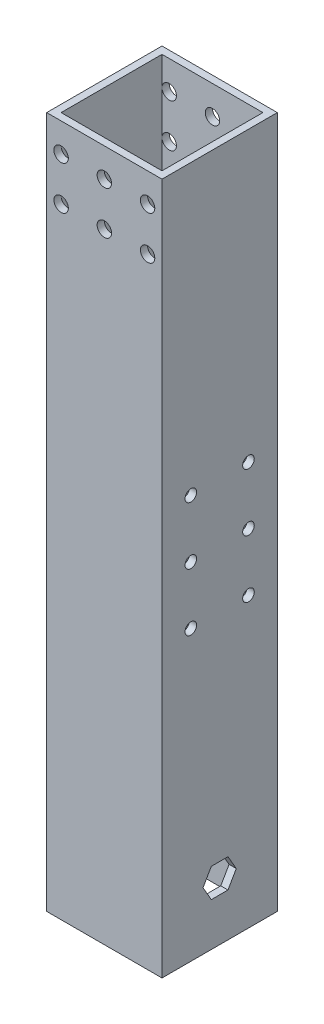
SolidWorks part; units mm, degrees
ref_plane "Front Plane" through (0, 0, 0) normal (0, 0, 1) x (1, 0, 0)
ref_plane "Top Plane" through (0, 0, 0) normal (0, 1, 0) x (1, 0, 0)
ref_plane "Right Plane" through (0, 0, 0) normal (1, 0, 0) x (0, 0, -1)
sketch "Sketch1" plane through (0, 0, 0) normal (0, 1, 0) x (1, 0, 0)
  line L1 (-25.4, -25.4) -> (25.4, -25.4)
  line L2 (-25.4, -25.4) -> (-25.4, 25.4)
  line L3 (-25.4, 25.4) -> (25.4, 25.4)
  line L4 (25.4, -25.4) -> (25.4, 25.4)
  line L5 (-25.4, -25.4) -> (25.4, 25.4) construction
  line L6 (-25.4, 25.4) -> (25.4, -25.4) construction
  line L7 (-22.225, -22.225) -> (22.225, -22.225)
  line L8 (-22.225, -22.225) -> (-22.225, 22.225)
  line L9 (-22.225, 22.225) -> (22.225, 22.225)
  line L10 (22.225, -22.225) -> (22.225, 22.225)
  line L11 (-22.225, -22.225) -> (22.225, 22.225) construction
  line L12 (-22.225, 22.225) -> (22.225, -22.225) construction
  point P0 (0, 0)
  point P6 (0, 0)
  dimension "D1" = 50.8
  dimension "D2" = 50.8
  dimension "D3" = 3.175
extrude "Boss-Extrude1" add sketch "Sketch1" along normal blind 304.8
sketch "Sketch2" plane through (0, 0, 25.4) normal (0, 0, 1) x (1, 0, 0)
  line L0 (-25.4, 304.8) -> (-25.4, 0) construction
  line L1 (-25.4, 304.8) -> (25.4, 304.8) construction
  circle A0 centre (-19.05, 292.1) radius 3.175
  dimension "D1" = 6.35
  dimension "D2" = 6.35
  dimension "D3" = 12.7
extrude "Cut-Extrude1" cut sketch "Sketch2" against normal blind 101.6
pattern_linear "LPattern1" count 3 spacing 19.05 along (1, 0, 0) count 2 spacing 19.05 along (0, -1, 0) of "Cut-Extrude1"
sketch "Sketch3" plane through (25.4, 0, 0) normal (1, 0, 0) x (0, 0, -1)
  line L0 (-25.4, 0) -> (25.4, 0) construction
  line L1 (-3.6662, 19.05) -> (3.6662, 19.05)
  line L2 (3.6662, 19.05) -> (7.3323, 25.4)
  line L3 (7.3323, 25.4) -> (3.6662, 31.75)
  line L4 (3.6662, 31.75) -> (-3.6662, 31.75)
  line L5 (-3.6662, 31.75) -> (-7.3323, 25.4)
  line L6 (-7.3323, 25.4) -> (-3.6662, 19.05)
  line L7 (25.4, 304.8) -> (25.4, 0) construction
  circle A0 centre (0, 25.4) radius 6.35 construction
  dimension "D1" = 12.7
  dimension "D2" = 0
  dimension "D3" = 25.4
  dimension "D4" = 25.4
extrude "Cut-Extrude2" cut sketch "Sketch3" against normal through all
sketch "Sketch4" plane through (25.4, 0, 0) normal (1, 0, 0) x (0, 0, -1)
  line L0 (-25.4, 304.8) -> (-25.4, 0) construction
  line L1 (-25.4, 304.8) -> (25.4, 304.8) construction
  circle A0 centre (-12.7, 177.8) radius 2.5527
  dimension "D1" = 5.1054
  dimension "D2" = 12.7
  dimension "D3" = 127
extrude "Cut-Extrude3" cut sketch "Sketch4" against normal blind 50.8
pattern_linear "LPattern2" count 3 spacing 25.4 along (0, -1, 0) count 2 spacing 25.4 along (0, 0, -1) of "Cut-Extrude3"
